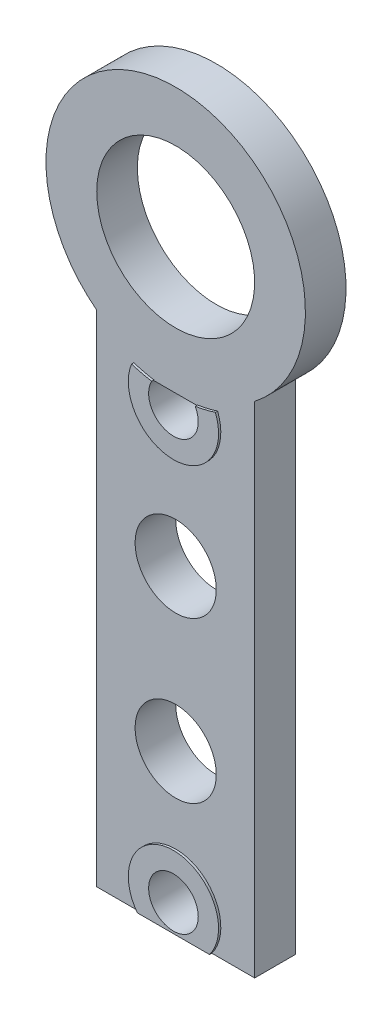
SolidWorks part; units mm, degrees
material "PVC Rigid"
ref_plane "Front Plane" through (0, 0, 0) normal (0, 0, 1) x (1, 0, 0)
ref_plane "Top Plane" through (0, 0, 0) normal (0, 1, 0) x (1, 0, 0)
ref_plane "Right Plane" through (0, 0, 0) normal (1, 0, 0) x (0, 0, -1)
sketch "Sketch1" plane through (0, 0, 0) normal (0, 0, 1) x (1, 0, 0)
  line L1 (-35.5187, -49.5) -> (-28.5187, -49.5)
  line L2 (-35.5187, -49.5) -> (-35.5187, -26.5)
  line L3 (-35.5187, -26.5) -> (-28.5187, -26.5)
  line L4 (-28.5187, -49.5) -> (-28.5187, -26.5)
extrude "Retainer_plate" add sketch "Sketch1" along normal blind 1.8 from offset 33.1
sketch "Sketch2" plane through (0, 0, 0) normal (0, 0, 1) x (1, 0, 0)
  circle A0 centre (-32.0187, -47.5) radius 2
  circle A1 centre (-32.0187, -28.5) radius 2
extrude "Retainer_mounting_spacers" add sketch "Sketch2" along normal blind 0.1 from offset 34.9
sketch "Sketch3" plane through (0, 0, 0) normal (0, 0, 1) x (1, 0, 0)
  circle A0 centre (-32.0187, -41.7454) radius 1.7
  circle A1 centre (-32.0187, -34.6434) radius 1.7
  circle A2 centre (-32.0187, -47.5) radius 1.1
  circle A3 centre (-32.0187, -28.5) radius 1.1
extrude "Retainer_clearance_holes" cut sketch "Sketch3" along normal blind 6 from offset 32
sketch "Sketch4" plane through (0, 0, 0) normal (0, 0, 1) x (1, 0, 0)
  line L0 (-40, -55) -> (-25, -55)
  line L1 (-25, -55) -> (-25, -48.7)
  line L2 (-25, -48.7) -> (-40, -48.7)
  line L3 (-40, -48.7) -> (-40, -55)
extrude "Clear_end_wall" cut sketch "Sketch4" along normal blind 6 from offset 33
sketch "Sketch5" plane through (0, 0, 0) normal (0, 0, 1) x (1, 0, 0)
  line L0 (-35.5187, -28) -> (-28.5187, -28)
  line L1 (-28.5187, -28) -> (-28.5187, -22)
  line L2 (-28.5187, -22) -> (-35.5187, -22)
  line L3 (-35.5187, -22) -> (-35.5187, -28)
extrude "Thumb_mount_extension" add sketch "Sketch5" along normal blind 1.8 from offset 33.1
sketch "Sketch6" plane through (0, 0, 0) normal (0, 0, 1) x (1, 0, 0)
  circle A0 centre (-32.0187, -22) radius 5.75
extrude "Thumb_mount_pad" add sketch "Sketch6" along normal blind 1.8 from offset 33.1
sketch "Sketch7" plane through (0, 0, 0) normal (0, 0, 1) x (1, 0, 0)
  circle A0 centre (-32.0187, -22) radius 3.5
extrude "Thumb_clearance_D7" cut sketch "Sketch7" along normal blind 2.5 from offset 32.8
sketch "Sketch8" plane through (0, 0, 0) normal (0, 0, 1) x (1, 0, 0)
  circle A0 centre (-32.0187, -22) radius 6.05
extrude "Clear_legacy_spacer_from_thumb_boss" cut sketch "Sketch8" along normal blind 2.3 from offset 34.9
sketch "Sketch9" plane through (0, 0, 0) normal (0, 0, 1) x (1, 0, 0)
  circle A0 centre (-32.0187, -41.7454) radius 1.8
extrude "Free_sliding_button_lower_guide_D3p6" cut sketch "Sketch9" along normal blind 2 from offset 33
sketch "Sketch10" plane through (0, 0, 0) normal (0, 0, 1) x (1, 0, 0)
  circle A0 centre (-32.0187, -34.6434) radius 1.8
extrude "Cut-Extrude2" cut sketch "Sketch10" along normal blind 2 from offset 33
